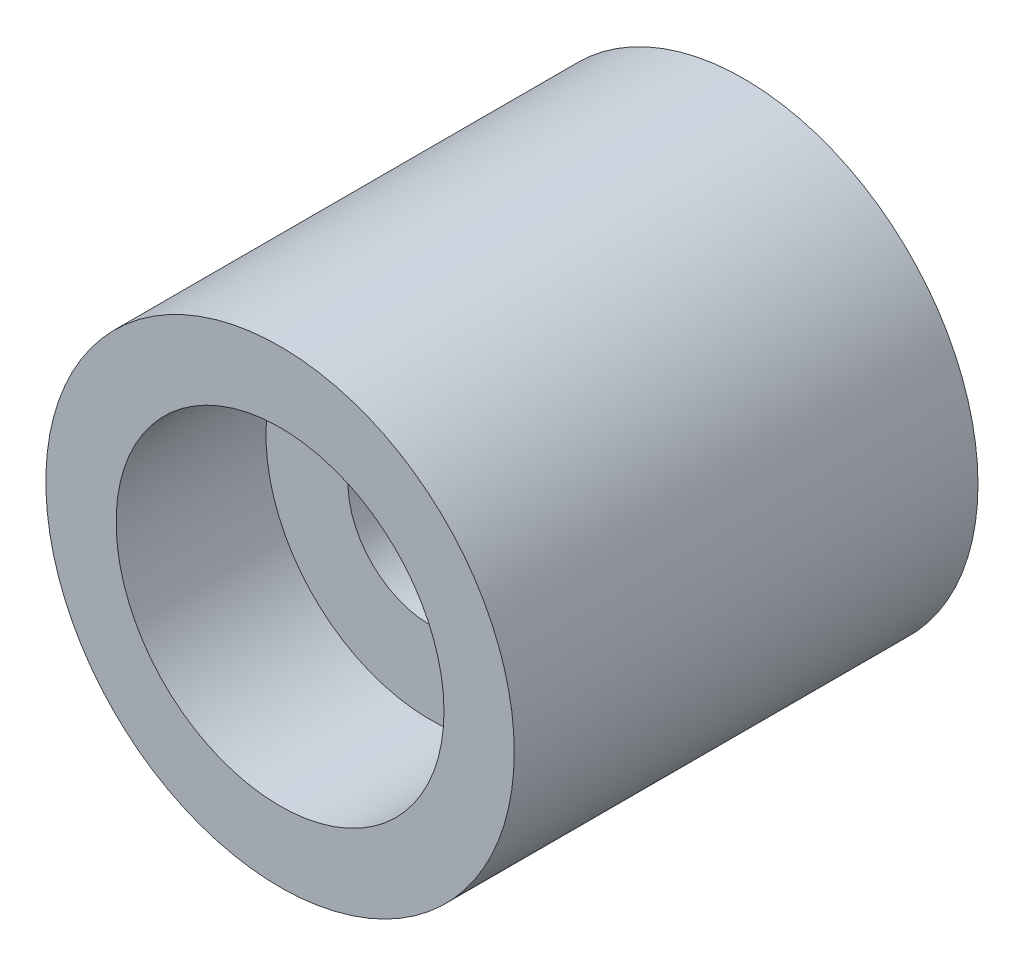
SolidWorks part; units mm, degrees
ref_plane "Front Plane" through (0, 0, 0) normal (0, 0, 1) x (1, 0, 0)
ref_plane "Top Plane" through (0, 0, 0) normal (0, 1, 0) x (1, 0, 0)
ref_plane "Right Plane" through (0, 0, 0) normal (1, 0, 0) x (0, 0, -1)
sketch "Sketch1" plane through (0, 0, 0) normal (0, 1, 0) x (1, 0, 0)
  line L0 (0, 0) -> (0, 12.3109) construction
  line L1 (-1.75, -1.75) -> (-1.75, 1.75)
  line L2 (-1.75, 1.75) -> (-3.5, 1.75)
  line L3 (-3.5, 1.75) -> (-3.5, 4.95)
  line L4 (-3.5, 4.95) -> (-5, 4.95)
  line L5 (-5, 4.95) -> (-5, -4.95)
  line L6 (-5, -4.95) -> (-3.5, -4.95)
  line L7 (-3.5, -4.95) -> (-3.5, -1.75)
  line L8 (-3.5, -1.75) -> (-1.75, -1.75)
  line L9 (-3.5, 1.75) -> (3.5, 1.75) construction
  line L10 (-3.5, 1.75) -> (3.5, 1.75) construction
  line L11 (3.5, 4.75) -> (-3.5, 4.75) construction
  line L12 (3.5, 4.75) -> (-3.5, 4.75) construction
  point P6 (-1.75, 0)
  dimension "D1" = 7
  dimension "D2" = 10
  dimension "D3" = 0.2
  dimension "D4" = 3.5
revolve "Revolve1" add sketch "Sketch1" angle 360 about L0
